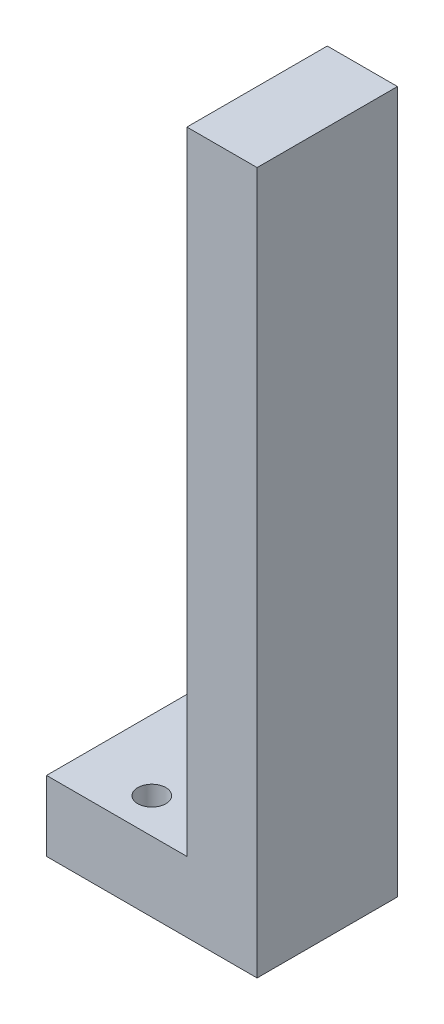
SolidWorks part; units mm, degrees
material "1060 Alloy"
ref_plane "Front Plane" through (0, 0, 0) normal (0, 0, 1) x (1, 0, 0)
ref_plane "Top Plane" through (0, 0, 0) normal (0, 1, 0) x (1, 0, 0)
ref_plane "Right Plane" through (0, 0, 0) normal (1, 0, 0) x (0, 0, -1)
sketch "Sketch1" plane through (0, 0, 0) normal (0, 0, 1) x (1, 0, 0)
  line L1 (-2.5, 25) -> (2.5, 25)
  line L2 (-2.5, 25) -> (-2.5, -25)
  line L3 (-2.5, -25) -> (2.5, -25)
  line L4 (2.5, 25) -> (2.5, -25)
  line L5 (-2.5, 25) -> (2.5, -25) construction
  line L6 (-2.5, -25) -> (2.5, 25) construction
  point P0 (0, 0)
  dimension "D1" = 50
  dimension "D2" = 5
extrude "Boss-Extrude1" add sketch "Sketch1" along normal mid plane 10 contours L1 L4 L3 L2
sketch "Sketch2" plane through (-2.5, 0, 0) normal (-1, 0, 0) x (0, 0, 1)
  line L0 (-5, 25) -> (-5, -25) construction
  line L1 (5, -25) -> (-5, -25)
  line L2 (5, -25) -> (5, -20)
  line L3 (5, -20) -> (-5, -20)
  line L4 (-5, -25) -> (-5, -20)
  dimension "D1" = 5
extrude "Boss-Extrude2" add sketch "Sketch2" along normal blind 10
sketch "Sketch3" plane through (0, -20, 0) normal (0, 1, 0) x (1, 0, 0)
  line L0 (-7.5, 5) -> (-7.5, -5) construction
  line L1 (-12.5, 5) -> (-2.5, 5) construction
  line L2 (-12.5, -5) -> (-2.5, -5) construction
  line L3 (-7.5, 2.5) -> (-7.5, -2.5) construction
  line L4 (-12.5, 0) -> (-2.5, 0) construction
  line L5 (-12.5, -5) -> (-12.5, 5) construction
  line L6 (-2.5, -5) -> (-2.5, 5) construction
  circle A0 centre (-7.5, 2.5) radius 1
  circle A1 centre (-7.5, -2.5) radius 1
  point P17 (-7.5, 0)
  dimension "D1" = 2
  dimension "D2" = 2
  dimension "D3" = 5
extrude "Cut-Extrude1" cut sketch "Sketch3" against normal through all
